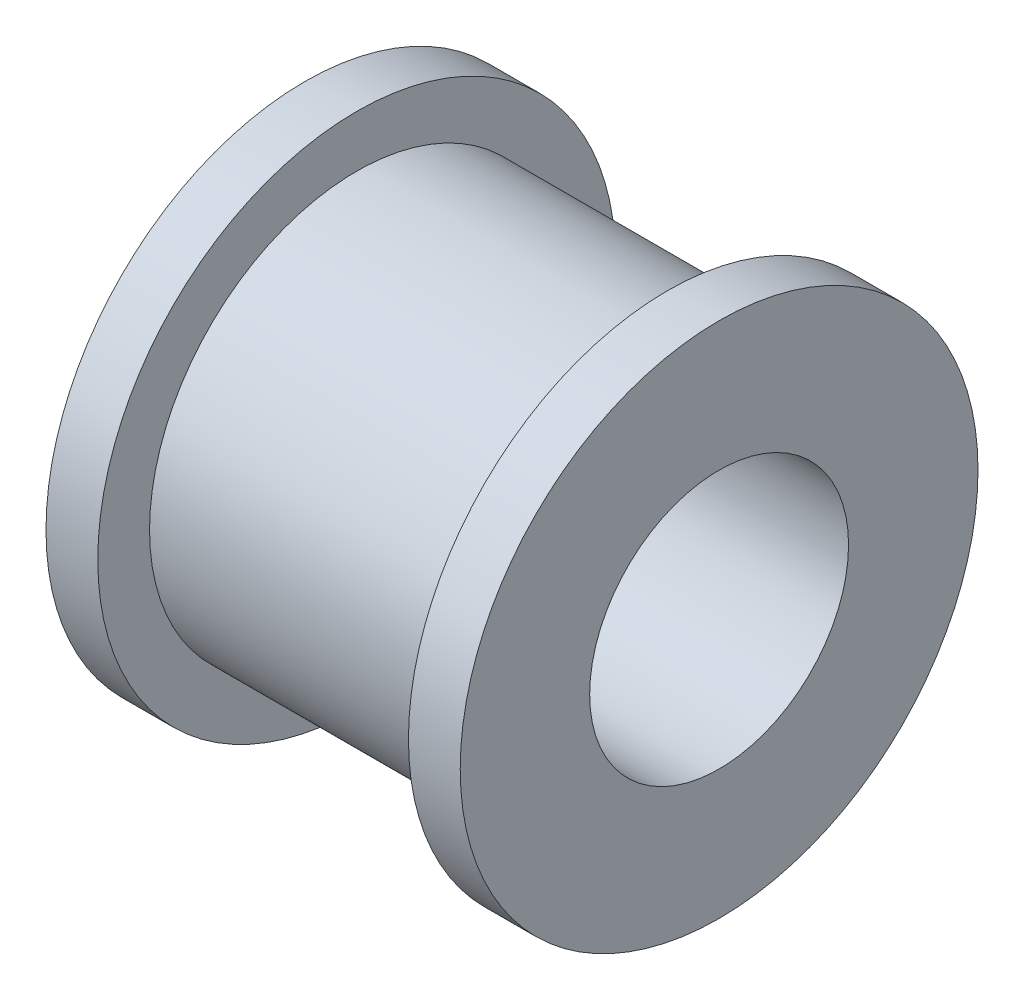
SolidWorks part; units mm, degrees
ref_plane "前视基准面" through (0, 0, 0) normal (0, 0, 1) x (1, 0, 0)
ref_plane "上视基准面" through (0, 0, 0) normal (0, 1, 0) x (1, 0, 0)
ref_plane "右视基准面" through (0, 0, 0) normal (1, 0, 0) x (0, 0, -1)
other "Configuration Table"
sketch "草图1" plane through (0, 0, 0) normal (1, 0, 0) x (0, 0, -1)
  circle A0 centre (0, 0) radius 2.5
  circle A1 centre (0, 0) radius 5
  dimension "D1" = 5
extrude "凸台-拉伸1" add sketch "草图1" along normal blind 8
ref_plane "基准面1" through (4, 0, 0) normal (1, 0, 0) x (0, 0, -1)
sketch "草图2" plane through (4, 0, 0) normal (1, 0, 0) x (0, 0, -1)
  circle A0 centre (0, 0) radius 4
  circle A1 centre (0, 0) radius 5
extrude "切除-拉伸1" cut sketch "草图2" against normal mid plane 6
